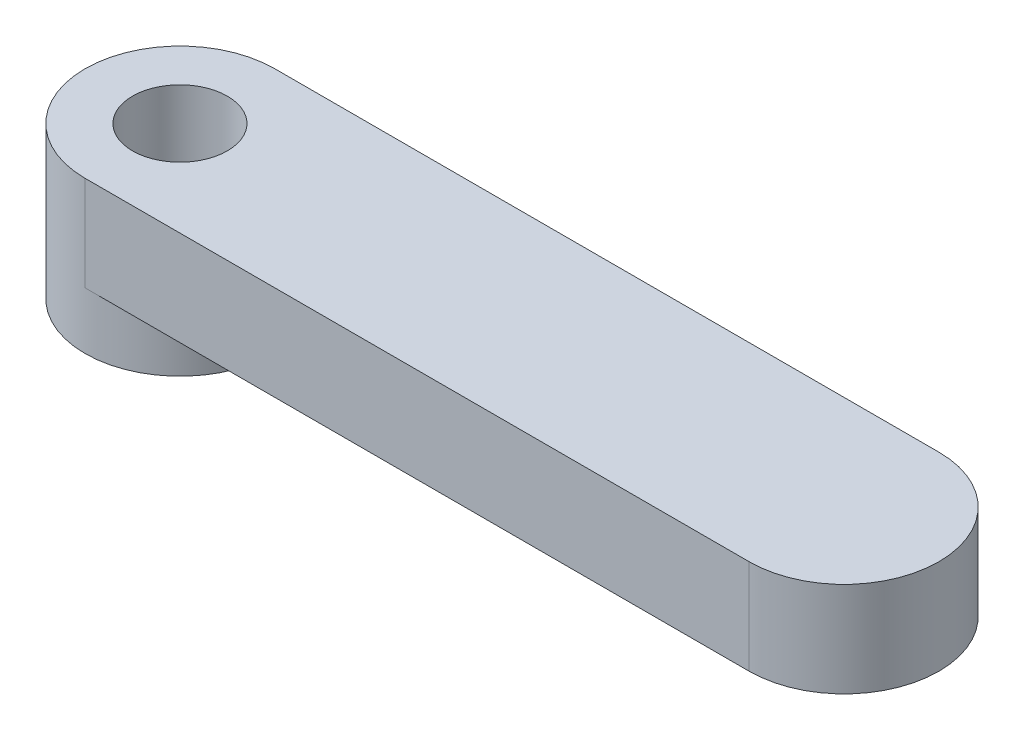
SolidWorks part; units mm, degrees
ref_plane "前视基准面" through (0, 0, 0) normal (0, 0, 1) x (1, 0, 0)
ref_plane "上视基准面" through (0, 0, 0) normal (0, 1, 0) x (1, 0, 0)
ref_plane "右视基准面" through (0, 0, 0) normal (1, 0, 0) x (0, 0, -1)
sketch "草图1" plane through (0, 0, 0) normal (0, 1, 0) x (1, 0, 0)
  line L0 (-34.3029, -11.0156) -> (0.6971, -11.0156) construction
  line L1 (-34.3029, -6.0156) -> (0.6971, -6.0156)
  line L2 (-34.3029, -16.0156) -> (0.6971, -16.0156)
  arc A0 (-34.3029, -6.0156) -> (-34.3029, -16.0156) centre (-34.3029, -11.0156) ccw
  arc A1 (0.6971, -16.0156) -> (0.6971, -6.0156) centre (0.6971, -11.0156) ccw
  circle A2 centre (-34.3029, -11.0156) radius 2.5
  point P2 (-16.8029, -11.0156)
  dimension "D3" = 5
  dimension "D1" = 10
  dimension "D2" = 35
extrude "凸台-拉伸1" add sketch "草图1" along normal blind 5
sketch "草图2" plane through (0, 0, 0) normal (0, -1, 0) x (1, 0, 0)
  circle A0 centre (-34.3029, 11.0156) radius 5
  circle A1 centre (-34.3029, 11.0156) radius 2.5
extrude "凸台-拉伸2" add sketch "草图2" along normal blind 3
